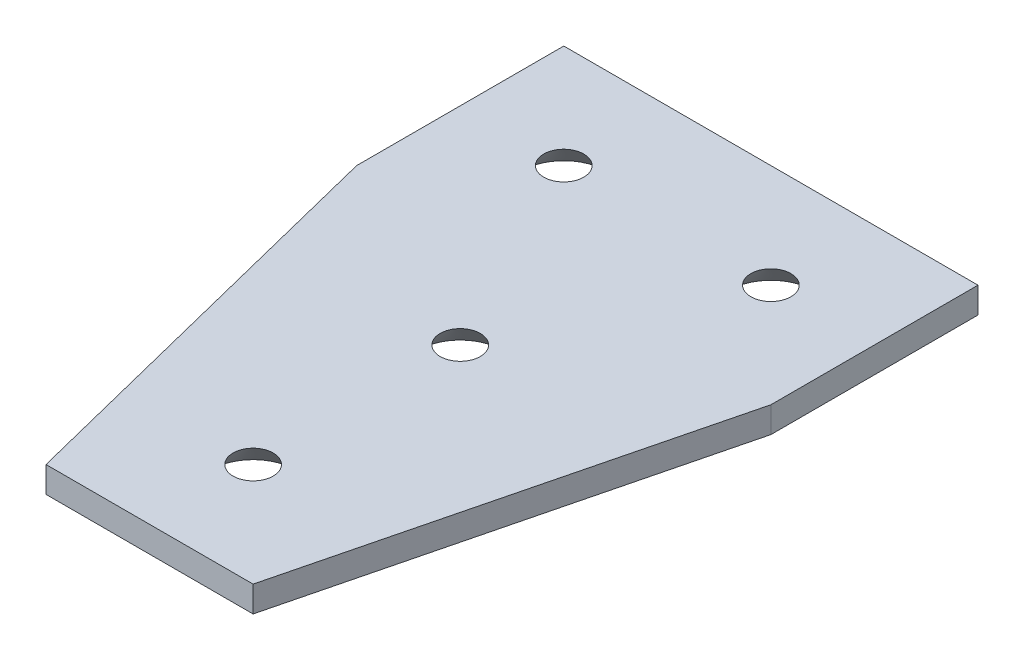
SolidWorks part; units mm, degrees
ref_plane "Front Plane" through (0, 0, 0) normal (0, 0, 1) x (1, 0, 0)
ref_plane "Top Plane" through (0, 0, 0) normal (0, 1, 0) x (1, 0, 0)
ref_plane "Right Plane" through (0, 0, 0) normal (1, 0, 0) x (0, 0, -1)
sketch "Sketch2" plane through (0, 0, 0) normal (0, 1, 0) x (1, 0, 0)
  line L2 (-0.3787, 269.2112) -> (50.4213, 269.2112)
  line L3 (-0.3787, 243.8112) -> (-0.3787, 269.2112)
  line L5 (50.4213, 269.2112) -> (50.4213, 243.8112)
  line L8 (-0.3787, 243.8112) -> (12.3213, 193.0112)
  line L9 (37.7213, 193.0112) -> (50.4213, 243.8112)
  line L11 (12.3213, 193.0112) -> (37.7213, 193.0112)
extrude "Boss-Extrude1" add sketch "Sketch2" along normal blind 3.175
sketch "Sketch5" plane through (0, 0, 0) normal (0, -1, 0) x (1, 0, 0)
  line L0 (25.0213, -269.2112) -> (25.0213, -256.5112) construction
  line L1 (50.4213, -269.2112) -> (-0.3787, -269.2112) construction
  line L2 (25.0213, -256.5112) -> (37.7213, -256.5112) construction
  line L3 (25.0213, -256.5112) -> (12.3213, -256.5112) construction
  line L4 (25.0213, -256.5112) -> (25.0213, -243.8112) construction
  line L5 (25.0213, -243.8112) -> (25.0213, -231.1112) construction
  line L6 (25.0213, -231.1112) -> (25.0213, -205.7112) construction
  point P7 (12.3213, -256.5112)
  point P8 (37.7213, -256.5112)
hole_wizard "#10 (0.1935) Diameter Hole1" positions "Sketch6" profile "Sketch7" hole size "#10" standard "ANSI Inch" end condition through all
sketch "Sketch6" plane through (0, 0, 0) normal (0, -1, 0) x (-1, 0, 0)
  point P0 (-37.7213, 256.5112)
  point P3 (-12.3213, 256.5112)
  point P6 (-25.0213, 231.1112)
  point P9 (-25.0213, 205.7112)
sketch "Sketch7" plane through (37.7213, 0, -256.5112) normal (1, 0, 0) x (0, 0, -1)
  line L0 (0, 0) -> (0, 3.175)
  line L1 (0, 3.175) -> (2.4574, 3.175)
  line L2 (2.4574, 3.175) -> (2.4574, 3.1776)
  line L3 (2.4574, 3.1776) -> (5.2197, 0)
  line L5 (5.2197, 0) -> (0, 0)
  line L6 (-2.4575, 3.1776) -> (-5.2197, 0) construction
  line L11 (0, -6.35) -> (0, 107.95) construction
  dimension "Thru Hole Dia." = 4.9149
  dimension "Thru Hole Depth" = 3.175
  dimension "Near C'Sink Dia." = 10.4394
  dimension "Near C'Sink Angle" = 82
